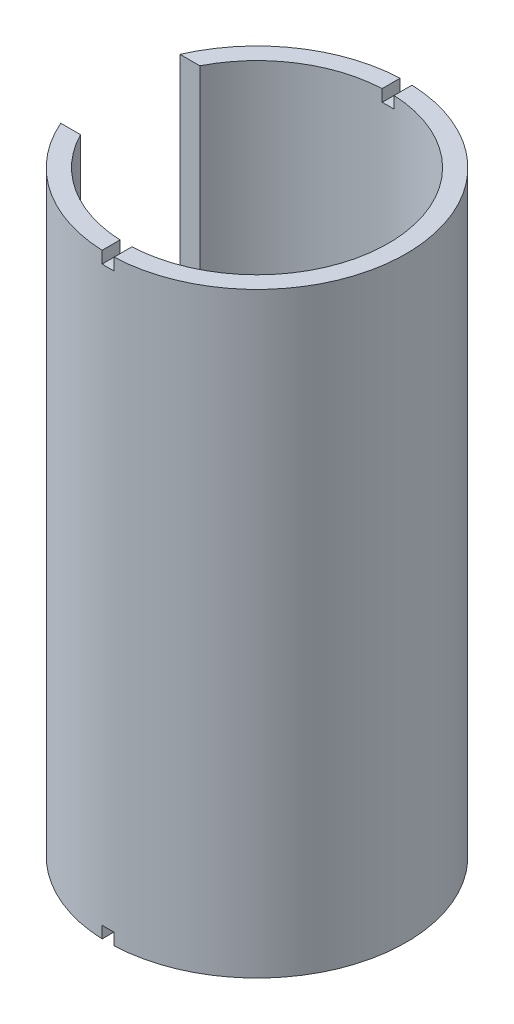
SolidWorks part; units mm, degrees
ref_plane "前基準面" through (0, 0, 0) normal (0, 0, 1) x (1, 0, 0)
ref_plane "上基準面" through (0, 0, 0) normal (0, 1, 0) x (1, 0, 0)
ref_plane "右基準面" through (0, 0, 0) normal (1, 0, 0) x (0, 0, -1)
sketch "草圖1" plane through (0, 0, 0) normal (0, 1, 0) x (1, 0, 0)
  circle A0 centre (0, 0) radius 22
  circle A1 centre (0, 0) radius 25
  dimension "D1" = 50
  dimension "D2" = 44
extrude "填料-伸長1" add sketch "草圖1" along normal blind 100
sketch "草圖2" plane through (0, 0, 0) normal (0, 0, 1) x (1, 0, 0)
  line L0 (22, 100) -> (-22, 100) construction
  line L1 (-1, 100) -> (1, 100)
  line L2 (-1, 100) -> (-1, 98)
  line L3 (-1, 98) -> (1, 98)
  line L4 (1, 100) -> (1, 98)
  line L5 (25, 100) -> (-25, 100) construction
  line L6 (-25, 0) -> (25, 0) construction
  line L7 (-1, 0) -> (1, 0)
  line L8 (-1, 0) -> (-1, 2)
  line L9 (-1, 2) -> (1, 2)
  line L10 (1, 0) -> (1, 2)
  point P19 (0, 0)
  dimension "D1" = 2
extrude "除料-伸長1" cut sketch "草圖2" against normal through all both and the other way through all
sketch "草圖3" plane through (0, 0, 0) normal (0, 1, 0) x (1, 0, 0)
  line L1 (-43.5913, 10) -> (-12.9392, 10)
  line L2 (-43.5913, 10) -> (-43.5913, -10)
  line L3 (-43.5913, -10) -> (-12.9392, -10)
  line L4 (-12.9392, 10) -> (-12.9392, -10)
  point P4 (-12.9392, 0)
  dimension "D1" = 20
extrude "除料-伸長4" cut sketch "草圖3" against normal through all and the other way through all contours L4 L1 L2 L3
